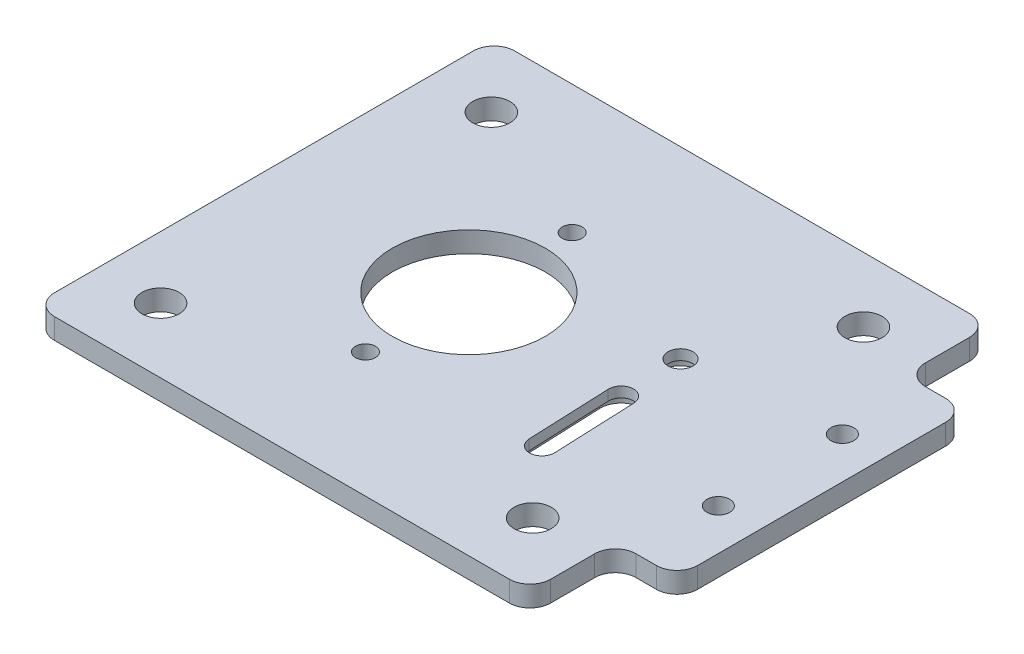
SolidWorks part; units mm, degrees
ref_plane "Front" through (0, 0, 0) normal (0, 0, 1) x (1, 0, 0)
ref_plane "Top" through (0, 0, 0) normal (0, 1, 0) x (1, 0, 0)
ref_plane "Right" through (0, 0, 0) normal (1, 0, 0) x (0, 0, -1)
sketch "Sketch1" plane through (0, 0, 0) normal (0, 1, 0) x (1, 0, 0)
  line L1 (0, 0) -> (230, 0)
  line L2 (0, 0) -> (0, 200)
  line L3 (0, 200) -> (230, 200)
  line L4 (230, 0) -> (230, 200)
  dimension "D1" = 200
  dimension "D2" = 230
extrude "Boss-Extrude1" add sketch "Sketch1" along normal blind 5
sketch "Sketch2" plane through (0, 5, 0) normal (0, 1, 0) x (1, 0, 0)
  line L0 (0, 102.5) -> (230, 102.5) construction
  line L1 (0, 200) -> (0, 0) construction
  line L2 (230, 200) -> (0, 200) construction
  line L3 (50, 60) -> (168.7171, 42.5) construction
  line L4 (102.3821, 72.4945) -> (96.5488, 32.9221) construction
  line L5 (104.3607, 72.2029) -> (98.5274, 32.6305)
  line L6 (100.4035, 72.7862) -> (94.5702, 33.2138)
  line L7 (0, 0) -> (230, 0) construction
  line L8 (50, 145) -> (169.8958, 150) construction
  line L9 (91.0069, 121.6884) -> (90.1736, 141.671) construction
  line L10 (94.0043, 121.8134) -> (93.171, 141.796)
  line L11 (88.0095, 121.5634) -> (87.1762, 141.546)
  line L12 (91.0069, 121.6884) -> (87.9496, 195.0012) construction
  circle A0 centre (50, 60) radius 15
  arc A2 (104.3607, 72.2029) -> (100.4035, 72.7862) centre (102.3821, 72.4945) ccw
  arc A3 (94.5702, 33.2138) -> (98.5274, 32.6305) centre (96.5488, 32.9221) ccw
  circle A4 centre (168.7171, 42.5) radius 14
  circle A5 centre (169.8958, 150) radius 10
  circle A6 centre (50, 145) radius 18.5
  arc A7 (94.0043, 121.8134) -> (88.0095, 121.5634) centre (91.0069, 121.6884) cw
  arc A8 (87.1762, 141.546) -> (93.171, 141.796) centre (90.1736, 141.671) cw
  circle A9 centre (89.5486, 156.658) radius 3
  point P13 (99.4655, 52.7083)
  point P29 (90.5903, 131.6797)
  dimension "D1" = 30
  dimension "D3" = 2
  dimension "D7" = 28
  dimension "D10" = 37
  dimension "D11" = 20
  dimension "D12" = 3
  dimension "D5" = 60
  dimension "D18" = 55
  dimension "D19" = 50
  dimension "D21" = 6
  dimension "D22" = 10
  dimension "D2" = 20
  dimension "D4" = 50
  dimension "D6" = 50
  dimension "D8" = 120
  dimension "D9" = 60
  dimension "D13" = 40
  dimension "D14" = 20
  dimension "D15" = 47.5
  dimension "D16" = 120
  dimension "D17" = 102.5
  dimension "D20" = 5
extrude "Cut-Extrude1" cut sketch "Sketch2" against normal through all
hole_wizard "M4 Clearance Hole1" positions "Sketch3" profile "Sketch4" hole size "M4" standard "ISO" end condition through all
sketch "Sketch3" plane through (0, 5, 0) normal (0, 1, 0) x (1, 0, 0)
  line L0 (0, 100) -> (137.9535, 100) construction
  line L1 (0, 200) -> (0, 0) construction
  circle A0 centre (50, 60) radius 27.5 construction
  circle A1 centre (168.7171, 42.5) radius 18.5 construction
  circle A2 centre (169.8958, 150) radius 29 construction
  circle A3 centre (50, 145) radius 25 construction
  circle A4 centre (50, 145) radius 18.5 construction
  point P9 (50, 32.5)
  point P21 (168.7171, 61)
  point P23 (168.7171, 24)
  point P25 (187.2171, 42.5)
  point P27 (150.2171, 42.5)
  point P37 (50, 170)
  point P38 (50, 120)
  dimension "D1" = 55
  dimension "D2" = 37
  dimension "D3" = 58
  dimension "D4" = 50
sketch "Sketch4" plane through (50, 5, -120) normal (1, 0, 0) x (0, 0, 1)
  line L0 (0, 0) -> (0, 5)
  line L1 (0, 5) -> (2.4, 5)
  line L2 (2.4, 5) -> (2.4, 0)
  line L5 (2.4, 0) -> (0, 0)
  line L11 (0, -6.35) -> (0, 107.95) construction
  dimension "Thru Hole Dia." = 4.8
  dimension "Thru Hole Depth" = 5
ref_plane "Plane1" through (0, 0, -100) normal (0, 0, 1) x (1, 0, 0)
sketch "Sketch5" plane through (0, 5, 0) normal (0, 1, 0) x (1, 0, 0)
  line L0 (-14.3101, 5) -> (264.9413, 5) construction
  line L1 (0, 0) -> (230, 0) construction
  line L2 (20, 5) -> (40, 5)
  line L3 (20, 5) -> (20, 10)
  line L4 (20, 10) -> (40, 10)
  line L5 (40, 5) -> (40, 10)
  line L6 (0, 200) -> (0, 0) construction
  line L7 (60, 5) -> (60, 10)
  line L8 (60, 5) -> (80, 5)
  line L9 (80, 5) -> (80, 10)
  line L10 (60, 10) -> (80, 10)
  line L11 (100, 5) -> (100, 10)
  line L12 (100, 5) -> (120, 5)
  line L13 (120, 5) -> (120, 10)
  line L14 (100, 10) -> (120, 10)
  line L15 (140, 5) -> (140, 10)
  line L16 (140, 5) -> (160, 5)
  line L17 (160, 5) -> (160, 10)
  line L18 (140, 10) -> (160, 10)
  line L19 (180, 5) -> (180, 10)
  line L20 (180, 5) -> (200, 5)
  line L21 (200, 5) -> (200, 10)
  line L22 (180, 10) -> (200, 10)
  line L23 (-19.5359, 56) -> (280.8716, 56) construction
  dimension "D1" = 5
  dimension "D2" = 20
  dimension "D3" = 5
  dimension "D4" = 20
  dimension "D6" = 51
  dimension "D5" = 5
extrude "Cut-Extrude2" cut sketch "Sketch5" against normal through all
ref_plane "Plane2" through (0, 0, -56) normal (0, 0, 1) x (1, 0, 0)
mirror "Slots" [suppressed] about plane through (0, 0, -56) normal (0, 0, 1)
mirror "Mirror2" [suppressed] about plane through (0, 0, -100) normal (0, 0, 1)
sketch "Sketch6" plane through (0, 5, 0) normal (0, 1, 0) x (1, 0, 0)
  line L0 (230, 100) -> (279.3216, 100) construction
  line L1 (230, 0) -> (230, 200) construction
  line L2 (168.3216, 160) -> (279.3216, 100) construction
  line L3 (193.9995, 123.3852) -> (213.0202, 158.5734) construction
  line L4 (192.2401, 124.3362) -> (211.2608, 159.5245)
  line L5 (195.7589, 122.4342) -> (214.7796, 157.6224)
  line L7 (-2.75, 100) -> (2.75, 100) construction
  arc A0 (192.2401, 124.3362) -> (195.7589, 122.4342) centre (193.9995, 123.3852) ccw
  arc A1 (214.7796, 157.6224) -> (211.2608, 159.5245) centre (213.0202, 158.5734) ccw
  point P8 (203.5099, 140.9793)
  dimension "D2" = 2
  dimension "D1" = 40
  dimension "D3" = 60
  dimension "D4" = 111
  dimension "D5" = 40
extrude "Cut-Extrude3" [suppressed] cut sketch "Sketch6" against normal through all
mirror "Mirror3" [suppressed] about plane through (0, 0, -100) normal (0, 0, 1)
sketch "Sketch8" plane through (0, 5, 0) normal (0, 1, 0) x (1, 0, 0)
  line L1 (0, 0) -> (230, 0)
  line L2 (0, 0) -> (0, 89.8)
  line L3 (0, 89.8) -> (230, 89.8)
  line L4 (230, 0) -> (230, 89.8)
  line L5 (-2.75, 100) -> (2.75, 100) construction
  dimension "D1" = 10.2
extrude "Cut-Extrude4" cut sketch "Sketch8" against normal through all
hole_wizard "M5 Clearance Hole1" [suppressed] positions "Sketch9" profile "Sketch10" hole size "M5" standard "ISO"
sketch "Sketch9" plane through (0, 5, 0) normal (0, 1, 0) x (1, 0, 0)
  point P0 (140.904, 149.8)
  point P3 (169.904, 178.8)
  point P6 (198.904, 149.8)
  point P9 (169.904, 120.8)
sketch "Sketch10" plane through (140.904, 5, -149.8) normal (1, 0, 0) x (0, 0, 1)
  line L0 (0, 0) -> (0, 5)
  line L1 (0, 5) -> (2.75, 5)
  line L2 (2.75, 5) -> (2.75, 0)
  line L5 (2.75, 0) -> (0, 0)
  line L11 (0, -6.35) -> (0, 107.95) construction
  dimension "Thru Hole Dia." = 5.5
  dimension "Thru Hole Depth" = 5
sketch "Sketch12" plane through (0, 5, 0) normal (0, 1, 0) x (1, 0, 0)
  line L0 (230, 89.8) -> (0, 89.8) construction
  line L1 (230, 200) -> (0, 200) construction
  line L2 (217.2641, 173.6991) -> (217.2641, 139.3226)
  line L3 (167.2641, 200) -> (167.2641, 221.1023)
  line L4 (167.2641, 221.1023) -> (280.3676, 221.1023)
  line L5 (280.3676, 221.1023) -> (280.3676, 67.4055)
  line L6 (280.3676, 67.4055) -> (160.3715, 67.4055)
  line L7 (160.3715, 67.4055) -> (160.3715, 89.8)
  arc A0 (160.3715, 89.8) -> (217.2641, 139.3226) centre (167.2641, 139.3226) ccw
  arc A1 (167.2641, 200) -> (217.2641, 173.6991) centre (167.2641, 139.3226) cw
  dimension "D1" = 50
extrude "Cut-Extrude5" [suppressed] cut sketch "Sketch12" against normal through all
fillet "Fillet1" [suppressed] radius 40
fillet "Fillet2" [suppressed] radius 80
sketch "Sketch16" plane through (0, 5, 0) normal (0, 1, 0) x (1, 0, 0)
  line L0 (120, 201.1) -> (120, 200)
  line L1 (0, 200) -> (120, 200)
  line L2 (0, 200) -> (0, 201.1)
  line L3 (0, 201.1) -> (120, 201.1)
  dimension "D1" = 1.1
  dimension "D2" = 120
extrude "Boss-Extrude2" add sketch "Sketch16" against normal up to surface (5 mm away) up to face at (115, 0, -144.9)
hole_wizard "M8 Clearance Hole1" positions "Sketch15" profile "Sketch14" hole size "M8" standard "ISO" end condition through all
sketch "Sketch15" plane through (0, 5, 0) normal (0, 1, 0) x (1, 0, 0)
  line L1 (0, 201.1) -> (0, 89.8) construction
  line L2 (8.4236, 145.45) -> (54.0921, 145.45) construction
  line L4 (60, 232.2025) -> (60, 74.9763) construction
  circle A0 centre (50, 145) radius 18.5 construction
  point P0 (15, 185.45)
  point P12 (15, 105.45)
  point P17 (105, 105.45)
  point P18 (105, 185.45)
  point P23 (0, 0)
  point P24 (53.8127, 150)
  point P25 (8.4236, 150)
  point P32 (54.0921, 145)
  dimension "D1" = 40
  dimension "D2" = 15
  dimension "D3" = 60
  dimension "D4" = 40.45
sketch "Sketch14" plane through (15, 5, -185.45) normal (1, 0, 0) x (0, 0, 1)
  line L0 (0, 0) -> (0, 5)
  line L1 (0, 5) -> (4.5, 5)
  line L2 (4.5, 5) -> (4.5, 0)
  line L5 (4.5, 0) -> (0, 0)
  line L11 (0, -6.35) -> (0, 107.95) construction
  dimension "Thru Hole Dia." = 9
  dimension "Thru Hole Depth" = 5
sketch "Sketch18" plane through (0, 5, 0) normal (0, 1, 0) x (1, 0, 0)
  line L0 (120, 225.9236) -> (254.2116, 225.9236)
  line L1 (254.2116, 225.9236) -> (254.2116, 61.3327)
  line L2 (254.2116, 61.3327) -> (120, 61.3327)
  line L3 (120, 225.9236) -> (120, 180.45)
  line L4 (120, 180.45) -> (195, 180.45)
  line L5 (195, 180.45) -> (195, 110.45)
  line L6 (195, 110.45) -> (120, 110.45)
  line L7 (120, 110.45) -> (120, 61.3327)
  line L8 (120, 200) -> (120, 201.1) construction
  line L9 (230, 200) -> (120, 200) construction
  line L11 (0, 201.1) -> (0, 89.8) construction
  dimension "D1" = 19.55
  dimension "D2" = 70
  dimension "D3" = 195
extrude "Cut-Extrude7" cut sketch "Sketch18" against normal through all
hole_wizard "M5 Clearance Hole2" positions "Sketch19" profile "Sketch21" hole size "M5" standard "ISO" end condition through all
sketch "Sketch19" plane through (0, 5, 0) normal (0, 1, 0) x (1, 0, 0)
  line L0 (124.9, 160.45) -> (124.9, 130.45) construction
  line L2 (124.9, 145.45) -> (195, 145.45) construction
  line L5 (195, 180.45) -> (195, 110.45) construction
  circle A0 centre (105, 185.45) radius 4.5 construction
  point P0 (124.9, 160.45)
  point P2 (124.9, 130.45)
  dimension "D1" = 30
  dimension "D2" = 19.9
sketch "Sketch21" plane through (124.9, 5, -160.45) normal (1, 0, 0) x (0, 0, 1)
  line L0 (0, 0) -> (0, 5)
  line L1 (0, 5) -> (2.75, 5)
  line L2 (2.75, 5) -> (2.75, 0)
  line L5 (2.75, 0) -> (0, 0)
  line L11 (0, -6.35) -> (0, 107.95) construction
  dimension "Thru Hole Dia." = 5.5
  dimension "Thru Hole Depth" = 5
fillet "Fillet3" radius 30 2 edges at (195, 2.5, -110.45) (195, 2.5, -180.45)
sketch "Sketch22" plane through (0, 5, 0) normal (0, 1, 0) x (1, 0, 0)
  line L0 (120, 110.45) -> (120, 89.8) construction
  line L1 (232.6427, 68.1793) -> (134.9, 68.1793)
  line L2 (232.6427, 68.1793) -> (232.6427, 219.9247)
  line L3 (232.6427, 219.9247) -> (134.9, 219.9247)
  line L4 (134.9, 68.1793) -> (134.9, 219.9247)
  dimension "D1" = 14.9
extrude "Cut-Extrude8" cut sketch "Sketch22" against normal through all
sketch "Sketch23" plane through (0, 0, 0) normal (0, -1, 0) x (1, 0, 0)
  line L16 (95.1693, -141.8793) -> (96.0026, -121.8967)
  line L17 (86.0113, -121.48) -> (85.1779, -141.4627)
  line L18 (95.1693, -141.8793) -> (96.0026, -121.8967)
  line L19 (86.0113, -121.48) -> (85.1779, -141.4627)
  arc A6 (85.1779, -141.4627) -> (95.1693, -141.8793) centre (90.1736, -141.671) ccw
  arc A7 (96.0026, -121.8967) -> (86.0113, -121.48) centre (91.0069, -121.6884) ccw
  arc A8 (85.1779, -141.4627) -> (95.1693, -141.8793) centre (90.1736, -141.671) ccw
  arc A9 (96.0026, -121.8967) -> (86.0113, -121.48) centre (91.0069, -121.6884) ccw
  circle A10 centre (89.5486, -156.658) radius 5
  circle A11 centre (89.5486, -156.658) radius 5
  dimension "D1" = 2
  dimension "D2" = 2
extrude "Cut-Extrude9" cut sketch "Sketch23" against normal blind 2.5
fillet "Fillet4" radius 5 8 edges at (120, 2.5, -89.8) (134.9, 2.5, -110.45) (120, 2.5, -110.45) (134.9, 2.5, -180.45) (120, 2.5, -180.45) (120, 2.5, -201.1) (0, 2.5, -201.1) (0, 2.5, -89.8)
